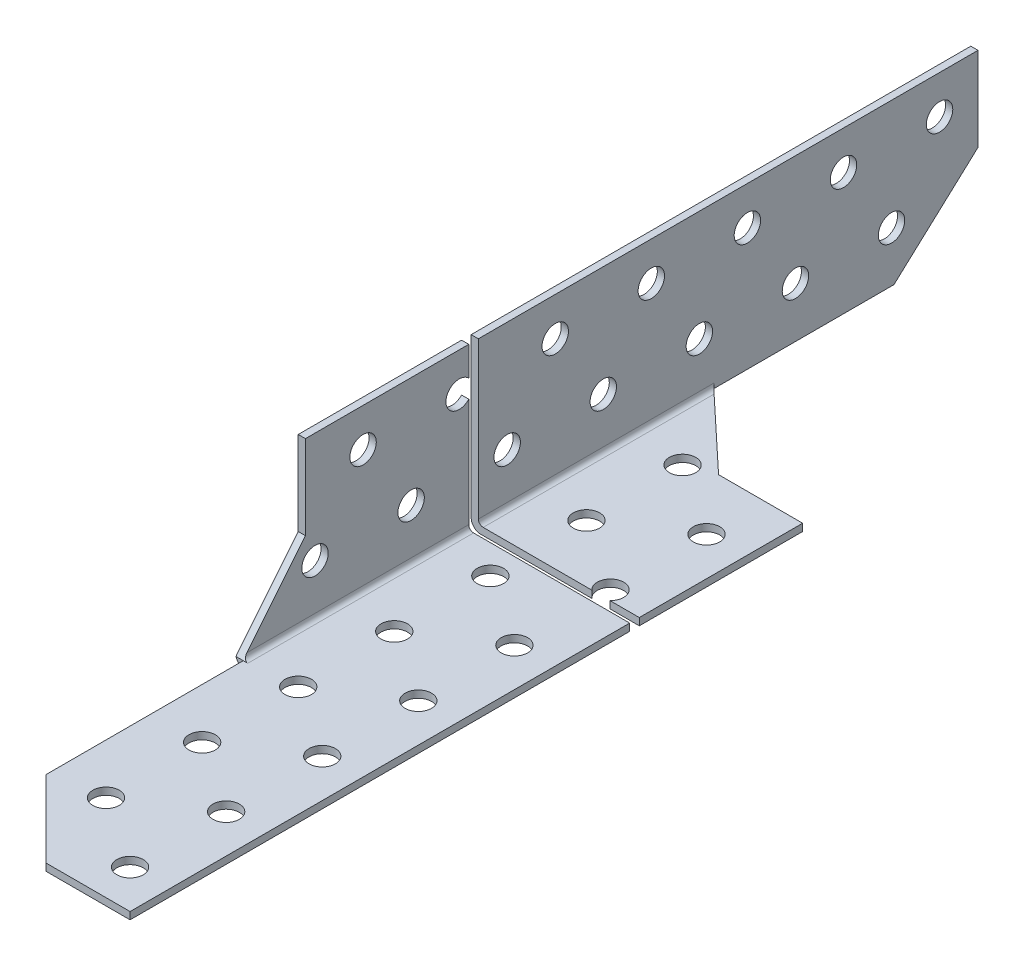
SolidWorks part; units mm, degrees
ref_plane "Płaszczyzna przednia" through (0, 0, 0) normal (0, 0, 1) x (1, 0, 0)
ref_plane "Płaszczyzna górna" through (0, 0, 0) normal (0, 1, 0) x (1, 0, 0)
ref_plane "Płaszczyzna prawa" through (0, 0, 0) normal (1, 0, 0) x (0, 0, -1)
sketch "Sketch1" plane through (0, 0, 0) normal (0, 0, 1) x (1, 0, 0)
  line L1 (-0.75, 17.5) -> (0.75, 17.5)
  line L2 (-0.75, 17.5) -> (-0.75, -17.5)
  line L3 (-0.75, -17.5) -> (0.75, -17.5)
  line L4 (0.75, 17.5) -> (0.75, -17.5)
  line L5 (-0.75, 17.5) -> (0.75, -17.5) construction
  line L6 (-0.75, -17.5) -> (0.75, 17.5) construction
  line L7 (-0.75, -17.5) -> (34.25, -17.5)
  line L8 (-0.75, -17.5) -> (-0.75, -16)
  line L9 (-0.75, -16) -> (34.25, -16)
  line L10 (34.25, -17.5) -> (34.25, -16)
  line L11 (-0.75, -17.5) -> (34.25, -16) construction
  line L12 (-0.75, -16) -> (34.25, -17.5) construction
  point P0 (0, 0)
  point P9 (16.75, -16.75)
  dimension "D1" = 1.5
  dimension "D2" = 35
  dimension "D3" = 1.5
  dimension "D4" = 35
extrude "Boss-Extrude1" add sketch "Sketch1" along normal blind 210 contours L2 L9 L4 L1 | L7 L10 L9 L4 | L9 L2 L3 L4
sketch "Sketch3" plane through (0.75, 0, 0) normal (1, 0, 0) x (0, 0, -1)
  line L0 (-140, 17.5) -> (-140, -16) construction
  line L1 (-210, 17.5) -> (0, 17.5) construction
  line L2 (-210, -16) -> (0, -16) construction
  line L3 (0, 17.5) -> (0, -16) construction
  line L4 (-140, 17.5) -> (-140, 0)
  line L5 (-153, 17.5) -> (-153, -16) construction
  line L6 (-210, 17.5) -> (-210, -16) construction
  line L7 (-153, -16) -> (-140, 0)
  line L8 (-140, 17.5) -> (-210, 17.5)
  line L9 (-210, 17.5) -> (-210, -16)
  line L10 (-210, -16) -> (-153, -16)
  line L11 (0, 0) -> (-17.5, -16)
  line L12 (-210, -16) -> (0, -16) construction
  line L13 (-17.5, -16) -> (-17.5, -36.8293)
  line L14 (-17.5, -36.8293) -> (0, -36.8293)
  line L15 (0, -36.8293) -> (0, 0)
  dimension "D1" = 140
  dimension "D2" = 17.5
  dimension "D3" = 57
  dimension "D4" = 17.5
extrude "Cut-Extrude2" cut sketch "Sketch3" against normal blind 62 and the other way blind 62
sketch "Sketch4" plane through (0, -16, 0) normal (0, 1, 0) x (1, 0, 0)
  line L0 (16.75, -210) -> (-0.75, -192.5)
  line L1 (-0.75, -210) -> (34.25, -210) construction
  line L2 (-0.75, -153) -> (-0.75, -210) construction
  line L3 (16.75, -210) -> (-0.75, -210)
  line L4 (-0.75, -210) -> (-0.75, -192.5)
  line L5 (34.25, -70) -> (0.75, -70) construction
  line L6 (34.25, -210) -> (34.25, -17.5) construction
  line L7 (0.75, -153) -> (0.75, -17.5) construction
  line L8 (34.25, -70) -> (16.75, -70)
  line L9 (16.75, -70) -> (0.75, -55)
  line L10 (0.75, -55) -> (0.75, -17.5)
  line L11 (0.75, -17.5) -> (34.25, -17.5)
  line L12 (34.25, -17.5) -> (34.25, -70)
  dimension "D1" = 17.5
  dimension "D2" = 140
  dimension "D3" = 17.5
  dimension "D4" = 155
extrude "Cut-Extrude3" cut sketch "Sketch4" against normal blind 62
sketch "Sketch5" plane through (0.75, 0, 0) normal (1, 0, 0) x (0, 0, -1)
  line L0 (0, 17.5) -> (0, 0) construction
  line L1 (-140, 17.5) -> (0, 17.5) construction
  line L2 (-8, 9.5) -> (-140, 9.5) construction
  line L3 (-140, 17.5) -> (-140, 0) construction
  line L4 (-144.4688, -5.5) -> (-6.0156, -5.5) construction
  line L5 (-140, 0) -> (-153, -16) construction
  line L6 (-17.5, -16) -> (0, 0) construction
  line L7 (-28, 9.5) -> (-28, -5.5) construction
  circle A0 centre (-8, 9.5) radius 2.75
  circle A1 centre (-28, 9.5) radius 2.75
  circle A2 centre (-48, 9.5) radius 2.75
  circle A3 centre (-68, 9.5) radius 2.75
  circle A4 centre (-88, 9.5) radius 2.75
  circle A5 centre (-108, 9.5) radius 2.75
  circle A6 centre (-128, 9.5) radius 2.75
  circle A7 centre (-18, -5.5) radius 2.75
  circle A8 centre (-38, -5.5) radius 2.75
  circle A9 centre (-58, -5.5) radius 2.75
  circle A10 centre (-78, -5.5) radius 2.75
  circle A11 centre (-98, -5.5) radius 2.75
  circle A12 centre (-118, -5.5) radius 2.75
  circle A13 centre (-138, -5.5) radius 2.75
  dimension "D1" = 8
  dimension "D3" = 20
  dimension "D12" = 20
  dimension "D2" = 8
  dimension "D4" = 20
  dimension "D5" = 20
  dimension "D6" = 20
  dimension "D7" = 20
  dimension "D8" = 20
  dimension "D9" = 12
  dimension "D10" = 8
  dimension "D11" = 23
  dimension "D13" = 20
  dimension "D14" = 20
  dimension "D15" = 20
  dimension "D16" = 20
  dimension "D17" = 20
  dimension "D18" = 10
extrude "Cut-Extrude4" cut sketch "Sketch5" against normal blind 5
fillet "Fillet1" radius 1 1 edges at (0.75, -16, 104)
fillet "Fillet2" radius 2 1 edges at (-0.75, -17.5, 105)
sketch "Sketch6" plane through (0.75, 0, 0) normal (1, 0, 0) x (0, 0, -1)
  line L1 (-55, -17.4365) -> (-17.5, -17.4365)
  line L2 (-55, -17.4365) -> (-55, -16)
  line L3 (-55, -16) -> (-17.5, -16)
  line L4 (-17.5, -17.4365) -> (-17.5, -16)
  line L5 (-55, -17.4365) -> (-17.5, -16) construction
  line L6 (-55, -16) -> (-17.5, -17.4365) construction
  point P4 (-36.25, -16.7182)
extrude "Cut-Extrude5" cut sketch "Sketch6" against normal blind 5
sketch "Sketch7" plane through (0, -16, 0) normal (0, 1, 0) x (1, 0, 0)
  line L1 (-0.6865, -153) -> (0.8135, -153)
  line L2 (-0.6865, -153) -> (-0.6865, -198.3598)
  line L3 (-0.6865, -198.3598) -> (0.8135, -198.3598)
  line L4 (0.8135, -153) -> (0.8135, -198.3598)
  line L5 (-0.6865, -153) -> (0.8135, -198.3598) construction
  line L6 (-0.6865, -198.3598) -> (0.8135, -153) construction
  point P4 (0.0635, -175.6799)
  dimension "D1" = 1.5
extrude "Cut-Extrude6" cut sketch "Sketch7" against normal blind 5
sketch "Sketch8" plane through (0, -16, 0) normal (0, 1, 0) x (1, 0, 0)
  line L0 (11.25, -72) -> (11.25, -201.8481) construction
  line L1 (26.25, -206.3168) -> (26.25, -67.8637) construction
  line L2 (11.25, -92) -> (26.25, -92) construction
  line L3 (34.25, -210) -> (34.25, -70) construction
  line L4 (16.75, -210) -> (34.25, -210) construction
  circle A0 centre (11.25, -72) radius 2.75
  circle A1 centre (11.25, -92) radius 2.75
  circle A2 centre (11.25, -112) radius 2.75
  circle A3 centre (11.25, -132) radius 2.75
  circle A4 centre (11.25, -152) radius 2.75
  circle A5 centre (11.25, -172) radius 2.75
  circle A6 centre (11.25, -192) radius 2.75
  circle A7 centre (26.25, -82) radius 2.75
  circle A8 centre (26.25, -102) radius 2.75
  circle A9 centre (26.25, -122) radius 2.75
  circle A10 centre (26.25, -142) radius 2.75
  circle A11 centre (26.25, -162) radius 2.75
  circle A12 centre (26.25, -182) radius 2.75
  circle A13 centre (26.25, -202) radius 2.75
  dimension "D1" = 20
  dimension "D2" = 20
  dimension "D3" = 20
  dimension "D4" = 20
  dimension "D5" = 20
  dimension "D6" = 20
  dimension "D7" = 20
  dimension "D8" = 20
  dimension "D9" = 20
  dimension "D10" = 20
  dimension "D11" = 20
  dimension "D12" = 20
  dimension "D13" = 10
  dimension "D14" = 8
  dimension "D15" = 23
  dimension "D16" = 15
  dimension "D17" = 8
extrude "Cut-Extrude7" cut sketch "Sketch8" against normal blind 5
sketch "Sketch10" plane through (0, -16, 0) normal (0, 1, 0) x (1, 0, 0)
  line L0 (34.25, -106) -> (-26.9278, -106) construction
  line L3 (34.25, -210) -> (34.25, -70) construction
  line L8 (16.75, -210) -> (34.25, -210) construction
  line L10 (34.25, -106) -> (-14.9261, -106)
  line L11 (34.25, -106) -> (34.25, -104)
  line L12 (34.25, -104) -> (-14.9261, -104)
  line L13 (-14.9261, -106) -> (-14.9261, -104)
  line L14 (34.25, -106) -> (-14.9261, -104) construction
  line L15 (34.25, -104) -> (-14.9261, -106) construction
  point P9 (9.6619, -105)
  dimension "D1" = 104
  dimension "D2" = 2
extrude "Cut-Extrude9" cut sketch "Sketch10" against normal blind 27 and the other way blind 49
other "Save Bodies1"
other "Save Bodies2"
